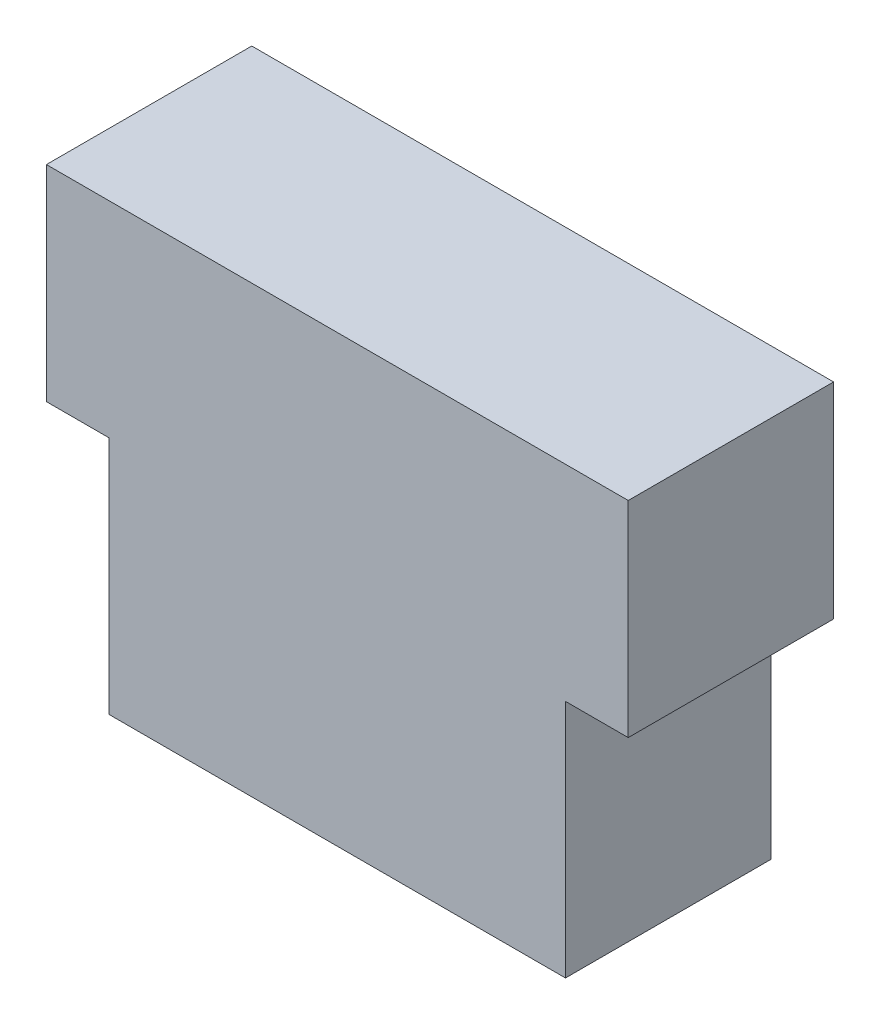
SolidWorks part; units mm, degrees
ref_plane "前视基准面" through (0, 0, 0) normal (0, 0, 1) x (1, 0, 0)
ref_plane "上视基准面" through (0, 0, 0) normal (0, 1, 0) x (1, 0, 0)
ref_plane "右视基准面" through (0, 0, 0) normal (1, 0, 0) x (0, 0, -1)
other "Configuration Table"
sketch "草图1" plane through (0, 0, 0) normal (0, 0, 1) x (1, 0, 0)
  line L0 (-20, 1.5) -> (-25.5, 1.5)
  line L1 (20, 19.5) -> (-20, 19.5)
  line L2 (20, 19.5) -> (20, -19.5)
  line L3 (20, -19.5) -> (-20, -19.5)
  line L4 (-20, 19.5) -> (-20, -19.5)
  line L5 (0, -19.5) -> (0, 19.5) construction
  line L6 (20, 0) -> (-20, 0) construction
  line L7 (20, 19.5) -> (25.5, 19.5)
  line L8 (20, 19.5) -> (20, 1.5)
  line L9 (20, 1.5) -> (25.5, 1.5)
  line L10 (25.5, 19.5) -> (25.5, 1.5)
  line L11 (-25.5, 19.5) -> (-25.5, 1.5)
  line L12 (-20, 19.5) -> (-25.5, 19.5)
  line L13 (-20, 19.5) -> (-20, 1.5)
  point P0 (0, 0)
  dimension "D1" = 40
  dimension "D2" = 39
  dimension "D3" = 5.5
  dimension "D4" = 18
extrude "凸台-拉伸1" add sketch "草图1" along normal blind 18 contours L1 L4 L3 L2 | L4 L12 L11 L0 | L10 L7 L2 L9
